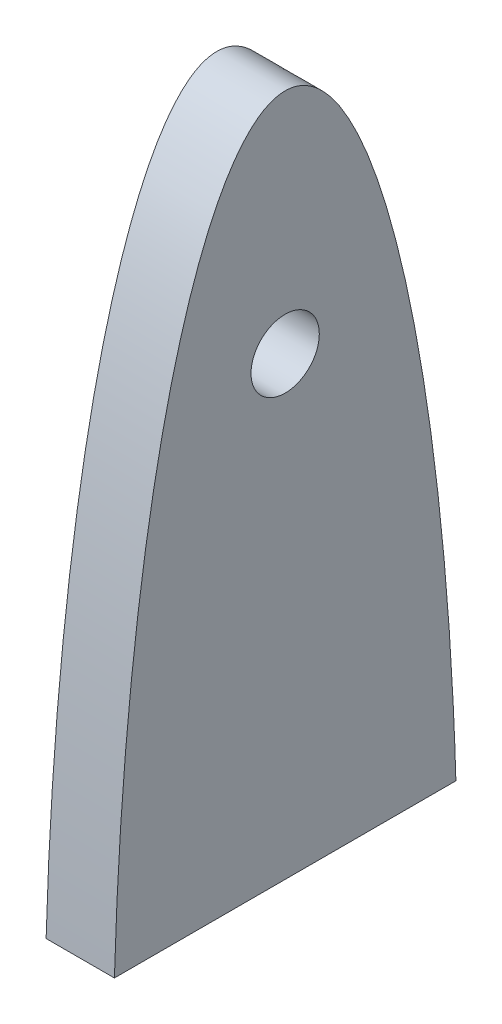
SolidWorks part; units mm, degrees
ref_plane "Front Plane" through (0, 0, 0) normal (0, 0, 1) x (1, 0, 0)
ref_plane "Top Plane" through (0, 0, 0) normal (0, 1, 0) x (1, 0, 0)
ref_plane "Right Plane" through (0, 0, 0) normal (1, 0, 0) x (0, 0, -1)
sketch "Sketch2" plane through (0, 0, 0) normal (1, 0, 0) x (0, 0, -1)
  line L0 (-7.5, 0) -> (7.5, 0) construction
  circle A0 centre (0, 20) radius 1.5
  conic Q0 (-7.5, 0) -> (7.5, 0) control (0, 250) rho 0.12
  point P6 (0, 26.4697)
  point P7 (0, 2.75)
  point P9 (0, 4.7053)
  point P10 (0, 12.8252)
  dimension "D4" = 3
  dimension "D1" = 15
  dimension "D2" = 30
  dimension "D3" = 250
  dimension "D5" = 20
extrude "Boss-Extrude1" add sketch "Sketch2" along normal blind 3 contours Q0 L0 A0
